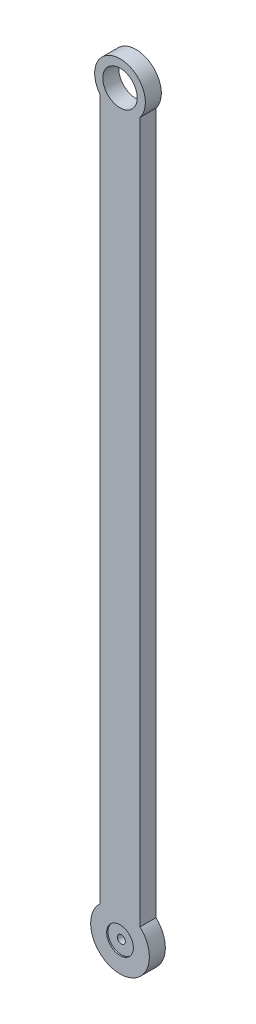
SolidWorks part; units mm, degrees
ref_plane "Plan de face" through (0, 0, 0) normal (0, 0, 1) x (1, 0, 0)
ref_plane "Plan de dessus" through (0, 0, 0) normal (0, 1, 0) x (1, 0, 0)
ref_plane "Plan de droite" through (0, 0, 0) normal (1, 0, 0) x (0, 0, -1)
sketch "Esquisse1" plane through (0, 0, 0) normal (0, 0, 1) x (1, 0, 0)
  line L1 (0, 0) -> (15, 0)
  line L2 (0, 0) -> (0, 290)
  line L3 (0, 290) -> (15, 290)
  line L4 (15, 0) -> (15, 290)
  dimension "D1" = 290
  dimension "D2" = 15
extrude "Boss.-Extru.1" add sketch "Esquisse1" along normal blind 6
sketch "Esquisse2" plane through (0, 0, 6) normal (0, 0, 1) x (1, 0, 0)
  line L0 (15, 0) -> (15, 290) construction
  line L1 (0, 0) -> (15, 0) construction
  line L2 (15, 290) -> (0, 290) construction
  line L3 (15, 0) -> (15, 290) construction
  circle A0 centre (7.5, 7.5) radius 11
  circle A1 centre (7.5, 284.25) radius 9.5
  dimension "D2" = 22
  dimension "D5" = 19
  dimension "D1" = 7.5
  dimension "D3" = 7.5
  dimension "D4" = 5.75
  dimension "D6" = 7.5
extrude "Boss.-Extru.2" add sketch "Esquisse2" against normal blind 6
sketch "Esquisse3" plane through (0, 0, 0) normal (0, 0, -1) x (-1, 0, 0)
  circle A0 centre (-7.5, 7.5) radius 1.5
  circle A1 centre (-7.5, 284.25) radius 6.45
  dimension "D1" = 3
  dimension "D2" = 12.9
extrude "Enlèv. mat.-Extru.1" cut sketch "Esquisse3" against normal blind 10
sketch "Esquisse4" plane through (0, 0, 6) normal (0, 0, 1) x (1, 0, 0)
  circle A0 centre (7.5, 7.5) radius 5
  dimension "D1" = 10
extrude "Enlèv. mat.-Extru.2" cut sketch "Esquisse4" against normal blind 0.5
